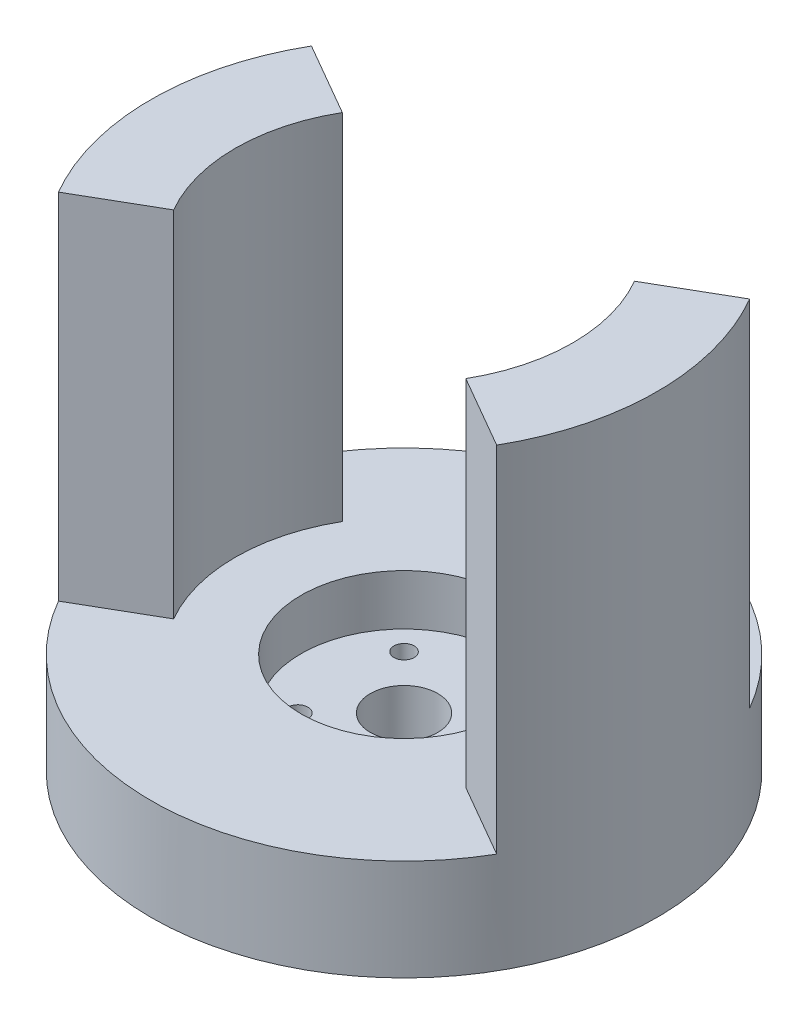
SolidWorks part; units mm, degrees
material "ABS"
ref_plane "Front Plane" through (0, 0, 0) normal (0, 0, 1) x (1, 0, 0)
ref_plane "Top Plane" through (0, 0, 0) normal (0, 1, 0) x (1, 0, 0)
ref_plane "Right Plane" through (0, 0, 0) normal (1, 0, 0) x (0, 0, -1)
sketch "Sketch1" plane through (0, 0, 0) normal (0, 1, 0) x (1, 0, 0)
  circle A0 centre (0, 0) radius 75
  dimension "D1" = 150
extrude "Boss-Extrude1" add sketch "Sketch1" along normal blind 30
sketch "Sketch2" plane through (0, 30, 0) normal (0, 1, 0) x (1, 0, 0)
  circle A0 centre (0, 0) radius 30.5
  dimension "D1" = 61
extrude "Cut-Extrude1" cut sketch "Sketch2" against normal blind 15
sketch "Sketch3" plane through (0, 30, 0) normal (0, 1, 0) x (1, 0, 0)
  line L0 (0, 0) -> (0, 80.13) construction
  line L1 (0, 0) -> (-87.6827, 50.6237) construction
  line L2 (0, 0) -> (96.1625, 55.5194) construction
  line L3 (0, 0) -> (0, -79.1993) construction
  line L4 (0, 0) -> (-83.8159, -48.3911) construction
  line L5 (0, 0) -> (72.515, -41.8666) construction
  line L6 (43.3013, 25) -> (64.9519, 37.5)
  line L7 (43.3013, -25) -> (64.9519, -37.5)
  line L8 (-43.3013, -25) -> (-64.9519, -37.5)
  line L9 (-43.3013, 25) -> (-64.9519, 37.5)
  circle A0 centre (0, 0) radius 75 construction
  arc A1 (-64.9519, 37.5) -> (-64.9519, -37.5) centre (0, 0) ccw
  arc A2 (64.9519, 37.5) -> (64.9519, -37.5) centre (0, 0) cw
  circle A3 centre (0, 0) radius 50 construction
  arc A4 (-43.3013, 25) -> (-43.3013, -25) centre (0, 0) ccw
  arc A5 (43.3013, 25) -> (43.3013, -25) centre (0, 0) cw
  point P7 (-64.9519, 37.5)
  point P11 (-64.9519, -37.5)
  point P12 (64.9519, 37.5)
  point P13 (64.9519, -37.5)
  point P19 (-43.3013, 25)
  point P20 (-43.3013, -25)
  point P21 (43.3013, 25)
  point P22 (43.3013, -25)
  dimension "D5" = 100
  dimension "D1" = 60
  dimension "D2" = 60
  dimension "D3" = 60
  dimension "D4" = 60
extrude "Boss-Extrude2" add sketch "Sketch3" along normal blind 105
sketch "Sketch4" plane through (0, 0, 0) normal (0, -1, 0) x (1, 0, 0)
  circle A0 centre (0, 0) radius 10
  dimension "D1" = 20
extrude "Cut-Extrude2" cut sketch "Sketch4" against normal blind 105
sketch "Sketch5" plane through (0, 0, 0) normal (0, -1, 0) x (1, 0, 0)
  line L0 (0, 0) -> (0, 80.5023) construction
  line L1 (0, 0) -> (96.6027, 0) construction
  line L2 (0, 0) -> (-98.6502, 0) construction
  line L3 (0, 0) -> (0, -80.5023) construction
  line L4 (0, 0) -> (65.7268, 65.7268) construction
  line L5 (0, 0) -> (-58.1417, 58.1417) construction
  line L6 (0, 0) -> (58.772, -58.772) construction
  line L7 (0, 0) -> (-65.2169, -65.2169) construction
  circle A0 centre (0, 0) radius 22.25 construction
  circle A1 centre (-15.7331, 15.7331) radius 3
  circle A2 centre (15.7331, 15.7331) radius 3
  circle A3 centre (15.7331, -15.7331) radius 3
  circle A4 centre (-15.7331, -15.7331) radius 3
  point P11 (15.7331, 15.7331)
  point P12 (15.7331, -15.7331)
  point P13 (-15.7331, -15.7331)
  point P14 (-15.7331, 15.7331)
  dimension "D5" = 6
  dimension "D6" = 6
  dimension "D7" = 6
  dimension "D8" = 6
  dimension "D1" = 45
  dimension "D2" = 45
  dimension "D3" = 45
  dimension "D4" = 45
extrude "Cut-Extrude3" cut sketch "Sketch5" against normal blind 105
